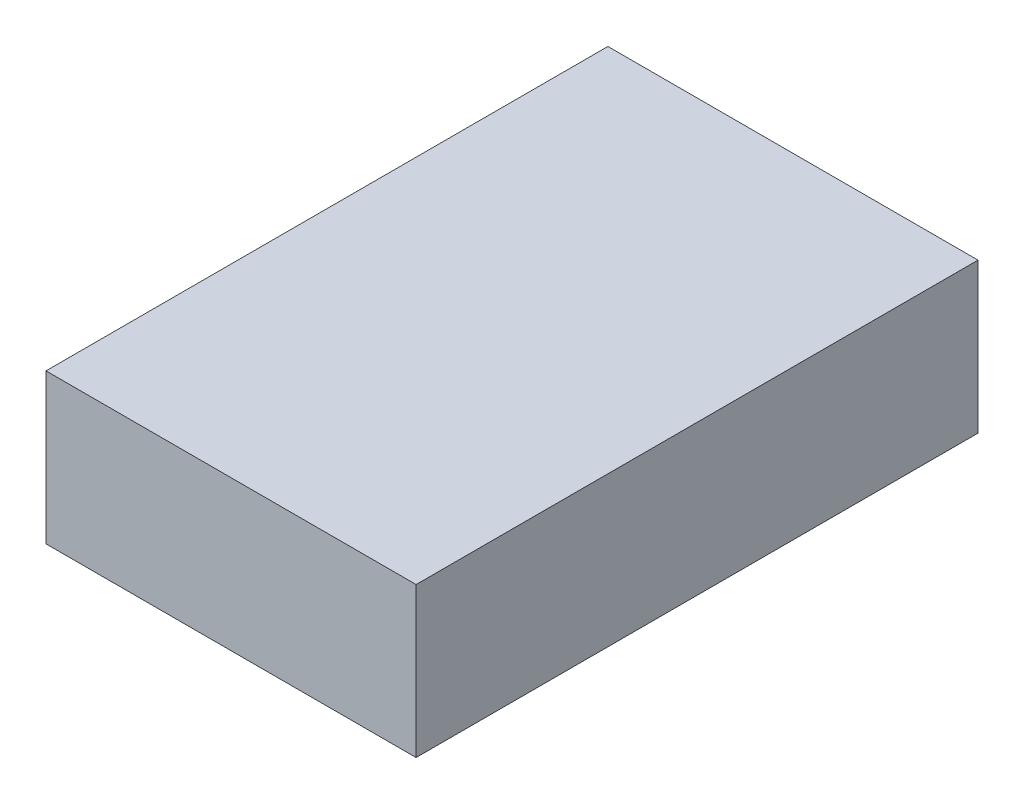
SolidWorks part; units mm, degrees
ref_plane "Front Plane" through (0, 0, 0) normal (0, 0, 1) x (1, 0, 0)
ref_plane "Top Plane" through (0, 0, 0) normal (0, 1, 0) x (1, 0, 0)
ref_plane "Right Plane" through (0, 0, 0) normal (1, 0, 0) x (0, 0, -1)
sketch "Sketch1" plane through (0, 0, 0) normal (0, 1, 0) x (1, 0, 0)
  line L1 (0, 15) -> (9.88, 15)
  line L2 (0, 15) -> (0, 0)
  line L3 (0, 0) -> (9.88, 0)
  line L4 (9.88, 15) -> (9.88, 0)
  dimension "D1" = 15
  dimension "D2" = 9.88
extrude "Boss-Extrude1" add sketch "Sketch1" along normal mid plane 4
ref_plane "Plane1" through (0, 2, 0) normal (1, 0, 0) x (0, 0, -1)
equation "\"Width\"= 15"
equation "\"Length\" = 9.88"
equation "\"D1@Sketch1\"=\"Width\""
equation "\"D2@Sketch1\"=\"Length\""
